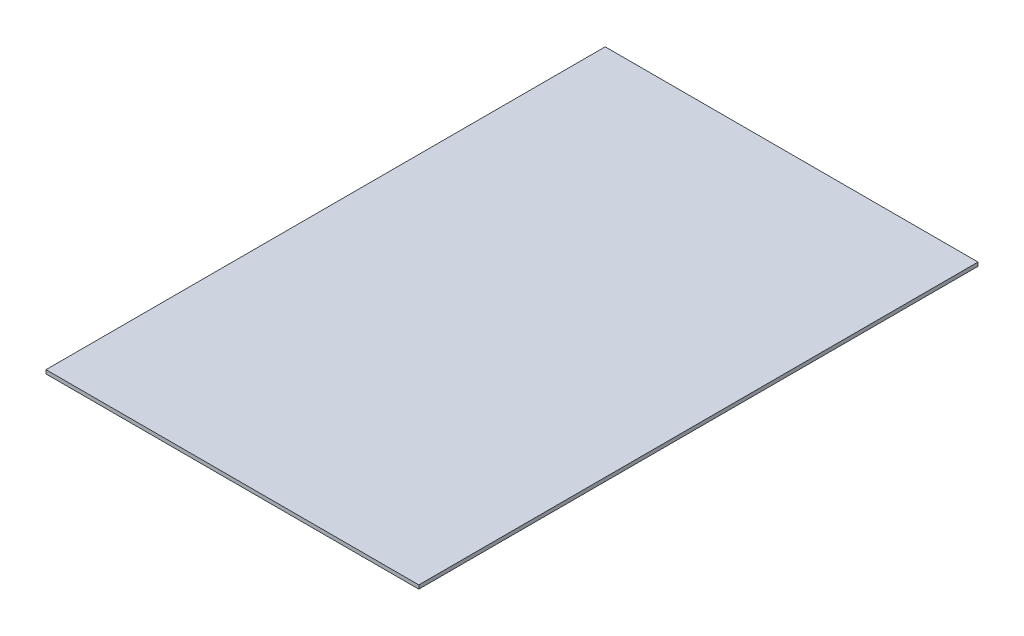
SolidWorks part; units mm, degrees
material "Plain Carbon Steel"
ref_plane "Front Plane" through (0, 0, 0) normal (0, 0, 1) x (1, 0, 0)
ref_plane "Top Plane" through (0, 0, 0) normal (0, 1, 0) x (1, 0, 0)
ref_plane "Right Plane" through (0, 0, 0) normal (1, 0, 0) x (0, 0, -1)
sketch "Sketch1" plane through (0, 0, 0) normal (0, 1, 0) x (1, 0, 0)
  line L1 (-127, 190.5) -> (127, 190.5)
  line L2 (-127, 190.5) -> (-127, -190.5)
  line L3 (-127, -190.5) -> (127, -190.5)
  line L4 (127, 190.5) -> (127, -190.5)
  line L5 (-127, 190.5) -> (127, -190.5) construction
  line L6 (-127, -190.5) -> (127, 190.5) construction
  point P0 (0, 0)
  dimension "D1" = 381
  dimension "D2" = 254
extrude "Boss-Extrude1" add sketch "Sketch1" along normal blind 2.54
